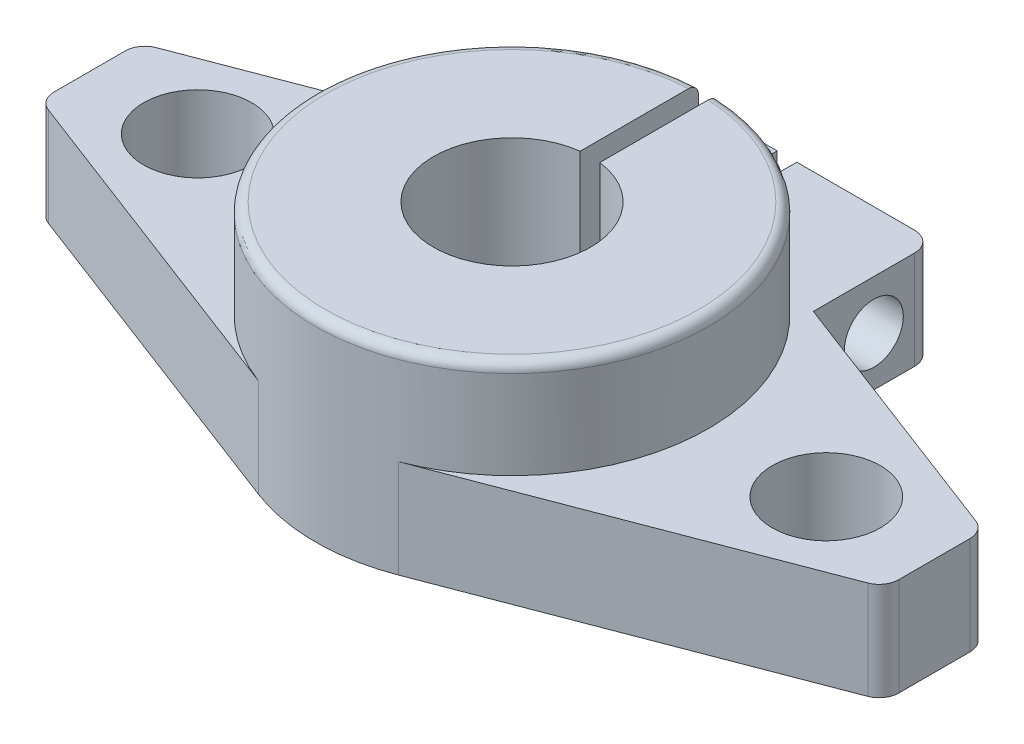
SolidWorks part; units mm, degrees
other "Kamera1"
ref_plane "Front Plane" through (0, 0, 0) normal (0, 0, 1) x (1, 0, 0)
ref_plane "Top Plane" through (0, 0, 0) normal (0, 1, 0) x (1, 0, 0)
ref_plane "Right Plane" through (0, 0, 0) normal (1, 0, 0) x (0, 0, -1)
sketch "Sketch1" plane through (0, 0, 0) normal (0, 1, 0) x (1, 0, 0)
  line L0 (0, 9.8473) -> (0, 0) construction
  line L1 (-21.5, 2.5) -> (-21.5, -2.5)
  line L2 (21.5, 2.5) -> (21.5, -2.5)
  line L3 (-26.3879, 0) -> (27.7491, 0) construction
  line L4 (-16, 9.8473) -> (-16, -13.603) construction
  line L5 (16, 9.8473) -> (16, -13.603) construction
  line L6 (-21.5, 2.5) -> (-7.5, 7.8416)
  line L7 (-21.5, -2.5) -> (-3.5648, -9.343)
  line L8 (21.5, -2.5) -> (3.5648, -9.343)
  line L9 (21.5, 2.5) -> (7.5, 7.8416)
  line L10 (-0.5, 9.9875) -> (-0.5, 3.9686)
  line L11 (21.5, 9.8473) -> (21.5, -13.603) construction
  line L12 (-21.5, 9.8473) -> (-21.5, -13.603) construction
  line L13 (0.5, 9.9875) -> (0.5, 3.9686)
  line L14 (0.5, 9.8473) -> (0.5, -13.603) construction
  line L15 (-0.5, 9.8473) -> (-0.5, -13.603) construction
  line L16 (-0.5, 9.9875) -> (-0.5, 14)
  line L17 (-0.5, 14) -> (-7.5, 14)
  line L18 (0, 9.8473) -> (0, -13.603) construction
  line L19 (-7.5, 14) -> (-7.5, 7.8416)
  line L21 (7.5, 14) -> (7.5, 7.8416)
  line L22 (0.5, 14) -> (7.5, 14)
  line L23 (0.5, 9.9875) -> (0.5, 14)
  arc A0 (-0.5, 3.9686) -> (0.5, 3.9686) centre (0, 0) ccw
  arc A1 (-3.5648, -9.343) -> (3.5648, -9.343) centre (0, 0) ccw
  circle A2 centre (-16, 0) radius 2.75
  circle A3 centre (16, 0) radius 2.75
  dimension "D1" = 8
  dimension "D4" = 20
  dimension "D7" = 5.5
  dimension "D9" = 5
  dimension "D10" = 2.5
  dimension "D11" = 7
  dimension "D2" = 0.5
  dimension "D3" = 21.5
  dimension "D5" = 16
extrude "Boss-Extrude1" add sketch "Sketch1" along normal blind 5
sketch "Sketch2" plane through (0, 5, 0) normal (0, 1, 0) x (1, 0, 0)
  line L0 (-0.5, 3.9686) -> (-0.5, 9.9875)
  line L4 (0.5, 9.9875) -> (0.5, 3.9686)
  arc A0 (-0.5, 3.9686) -> (0.5, 3.9686) centre (0, 0) ccw
  arc A1 (-0.5, 9.9875) -> (0.5, 9.9875) centre (0, 0) ccw
extrude "Boss-Extrude2" add sketch "Sketch2" along normal blind 5
fillet "Radyus2" radius 0.5 1 edges at (0, 10, 10)
fillet "Radyus3" radius 1 1 edges at (21.5, 2.5, 2.5)
fillet "Radyus4" radius 1 3 edges at (-21.5, 2.5, -2.5) (-21.5, 2.5, 2.5) (21.5, 2.5, -2.5)
sketch "Sketch3" plane through (7.5, 0, 0) normal (1, 0, 0) x (0, 0, -1)
  circle A0 centre (10.9208, 2.5) radius 1.5
  dimension "D1" = 3
extrude "Cut-Extrude1" cut sketch "Sketch3" against normal through all
fillet "Radyus5" radius 1 2 edges at (7.5, 2.5, -14) (-7.5, 2.5, -14)
